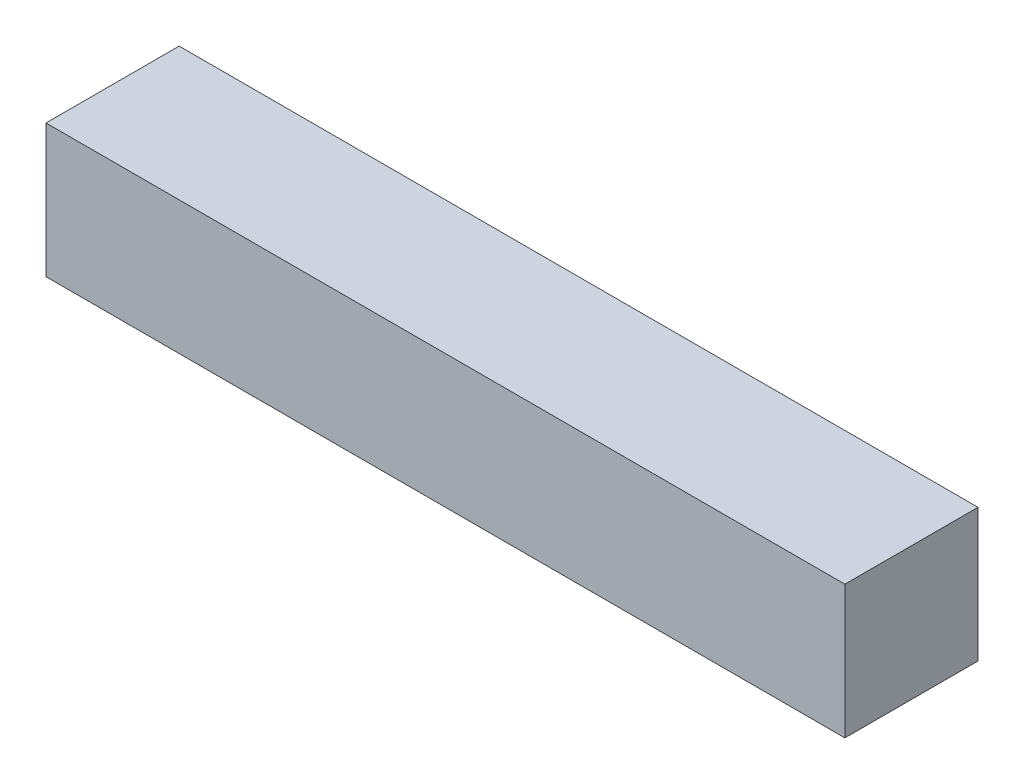
SolidWorks part; units mm, degrees
ref_plane "Front Plane" through (0, 0, 0) normal (0, 0, 1) x (1, 0, 0)
ref_plane "Top Plane" through (0, 0, 0) normal (0, 1, 0) x (1, 0, 0)
ref_plane "Right Plane" through (0, 0, 0) normal (1, 0, 0) x (0, 0, -1)
sketch "Sketch1" plane through (0, 0, 0) normal (1, 0, 0) x (0, 0, -1)
  line L1 (-5, 5) -> (5, 5)
  line L2 (-5, 5) -> (-5, -5)
  line L3 (-5, -5) -> (5, -5)
  line L4 (5, 5) -> (5, -5)
  line L5 (-5, 5) -> (5, -5) construction
  line L6 (-5, -5) -> (5, 5) construction
  point P0 (0, 0)
  dimension "D1" = 10
  dimension "D2" = 10
extrude "Boss-Extrude1" add sketch "Sketch1" along normal blind 60
